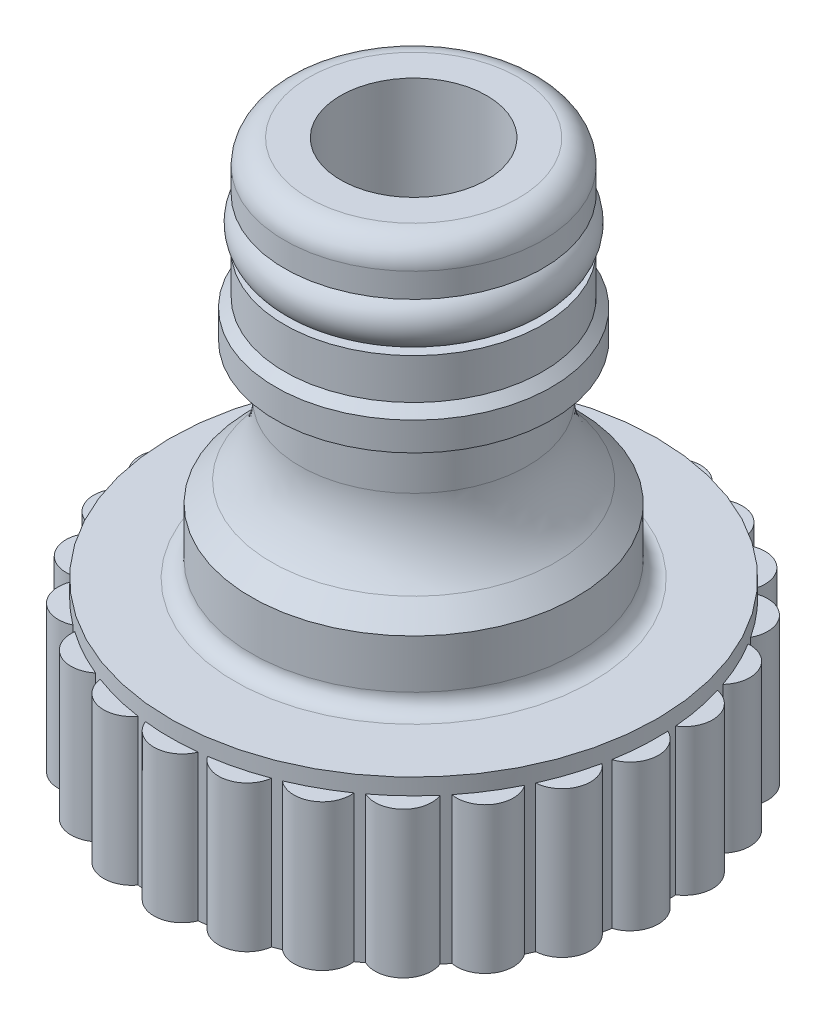
SolidWorks part; units mm, degrees
ref_plane "Front Plane" through (0, 0, 0) normal (0, 0, 1) x (1, 0, 0)
ref_plane "Top Plane" through (0, 0, 0) normal (0, 1, 0) x (1, 0, 0)
ref_plane "Right Plane" through (0, 0, 0) normal (1, 0, 0) x (0, 0, -1)
sketch "Sketch1" plane through (0, 0, 0) normal (0, 0, 1) x (1, 0, 0)
  line L0 (0, 0) -> (0, 23.5) construction
  line L1 (0, 23.5) -> (6.45, 23.5)
  line L2 (7.95, 22) -> (7.95, 15)
  line L3 (7.95, 15) -> (8.5, 14.45)
  line L4 (8.5, 14.45) -> (8.5, 12.7)
  line L5 (8.5, 12.7) -> (7.2887, 12.1352)
  line L6 (7, 11.682) -> (7, 9.4855)
  line L7 (8.757, 5.2432) -> (10, 4)
  line L8 (10, 4) -> (10, 0)
  line L9 (10, 0) -> (0, 0)
  line L10 (0, 0) -> (0, 23.5)
  arc A0 (8.757, 5.2432) -> (7, 9.4855) centre (13, 9.4855) cw
  arc A1 (7.95, 22) -> (6.45, 23.5) centre (6.45, 22) ccw
  arc A2 (7, 11.682) -> (7.2887, 12.1352) centre (7.5, 11.682) cw
  point P13 (7, 7.0005)
  point P16 (7.95, 23.5)
  point P19 (7, 12.0005)
  dimension "D12" = 6
  dimension "D13" = 1.5
  dimension "D14" = 0.5
  dimension "D2" = 10
  dimension "D3" = 4
  dimension "D4" = 7.95
  dimension "D5" = 8.5
  dimension "D6" = 8.5
  dimension "D7" = 135
  dimension "D8" = 1.75
  dimension "D9" = 115
  dimension "D10" = 7
  dimension "D11" = 5
  dimension "D15" = 19.5
revolve "Revolve1" add sketch "Sketch1" angle 360 about L0
sketch "Sketch2" plane through (0, 0, 0) normal (0, 0, 1) x (1, 0, 0)
  line L0 (0, 0) -> (0, 23.5) construction
  line L1 (6.45, 23.5) -> (-6.45, 23.5) construction
  line L2 (7.95, 15) -> (7.95, 22) construction
  line L3 (7.95, 20.5) -> (6.25, 20.5)
  line L4 (7.95, 20.5) -> (7.95, 17.5)
  line L5 (7.95, 17.5) -> (6.25, 17.5)
  line L6 (5.75, 20) -> (5.75, 18)
  arc A0 (5.75, 18) -> (6.25, 17.5) centre (6.25, 18) ccw
  arc A1 (5.75, 20) -> (6.25, 20.5) centre (6.25, 20) cw
  dimension "D4" = 0.5
  dimension "D1" = 3
  dimension "D2" = 3
  dimension "D3" = 5.75
revolve "Cut-Revolve1" cut sketch "Sketch2" angle 360 about L0
sketch "Sketch3" plane through (0, 0, 0) normal (0, 0, 1) x (1, 0, 0)
  line L0 (0, 0) -> (0, 23.5) construction
  line L1 (6.45, 23.5) -> (-6.45, 23.5) construction
  line L2 (0, 23.5) -> (4.5, 23.5)
  line L3 (4.5, 23.5) -> (4.5, 12.148)
  line L4 (-10, 0) -> (10, 0) construction
  line L5 (7, 0) -> (0, 0)
  line L6 (0, 0) -> (0, 23.5)
  arc A0 (4.5, 12.148) -> (7, 0) centre (35.2647, 12.148) ccw
  dimension "D1" = 4.5
  dimension "D2" = 7
revolve "Cut-Revolve2" cut sketch "Sketch3" angle 360 about L0
sketch "Sketch4" plane through (0, 0, 0) normal (0, -1, 0) x (1, 0, 0)
  circle A1 centre (0, 0) radius 14.9804
extrude "Boss-Extrude1" add sketch "Sketch4" along normal blind 10
sketch "Sketch5" plane through (0, -10, 0) normal (0, -1, 0) x (1, 0, 0)
  line L0 (0, 0) -> (0, 14.2444) construction
  circle A0 centre (0, 14.2444) radius 1.7466
  circle A1 centre (3.5424, 13.7968) radius 1.7466
  circle A2 centre (6.8623, 12.4824) radius 1.7466
  circle A3 centre (9.7509, 10.3837) radius 1.7466
  circle A4 centre (12.0269, 7.6325) radius 1.7466
  circle A5 centre (13.5472, 4.4017) radius 1.7466
  circle A6 centre (14.2162, 0.8944) radius 1.7466
  circle A7 centre (13.992, -2.6691) radius 1.7466
  circle A8 centre (12.8887, -6.065) radius 1.7466
  circle A9 centre (10.9755, -9.0797) radius 1.7466
  circle A10 centre (8.3726, -11.5239) radius 1.7466
  circle A11 centre (5.2437, -13.2441) radius 1.7466
  circle A12 centre (1.7853, -14.132) radius 1.7466
  circle A13 centre (-1.7853, -14.132) radius 1.7466
  circle A14 centre (-5.2437, -13.2441) radius 1.7466
  circle A15 centre (-8.3726, -11.5239) radius 1.7466
  circle A16 centre (-10.9755, -9.0797) radius 1.7466
  circle A17 centre (-12.8887, -6.065) radius 1.7466
  circle A18 centre (-13.992, -2.6691) radius 1.7466
  circle A19 centre (-14.2162, 0.8944) radius 1.7466
  circle A20 centre (-13.5472, 4.4017) radius 1.7466
  circle A21 centre (-12.0269, 7.6325) radius 1.7466
  circle A22 centre (-9.7509, 10.3837) radius 1.7466
  circle A23 centre (-6.8623, 12.4824) radius 1.7466
  circle A24 centre (-3.5424, 13.7968) radius 1.7466
  dimension "D1" = 25
extrude "Boss-Extrude2" add sketch "Sketch5" against normal blind 9
sketch "Sketch6" plane through (0, -10, 0) normal (0, -1, 0) x (1, 0, 0)
  circle A0 centre (0, 0) radius 12.3563
extrude "Cut-Extrude1" cut sketch "Sketch6" against normal blind 10 draft 27.651
fillet "Fillet3" radius 1 1 edges at (0, 0, -10)
sketch "Sketch7" plane through (0, 0, 0) normal (0, 0, 1) x (1, 0, 0)
  line L0 (0, 0) -> (0, 19) construction
  line L1 (0, 19) -> (8.25, 19) construction
  line L2 (6.65, 17.5) -> (6.65, 20.5) construction
  line L3 (7.95, 17.5) -> (-7.95, 17.5) construction
  line L4 (-7.95, 20.5) -> (7.95, 20.5) construction
  circle A0 centre (6.65, 19) radius 1.6
  point P12 (6.65, 19)
  dimension "D1" = 3.2
  dimension "D2" = 8.25
revolve "Revolve2" add sketch "Sketch7" angle 360 about L0
